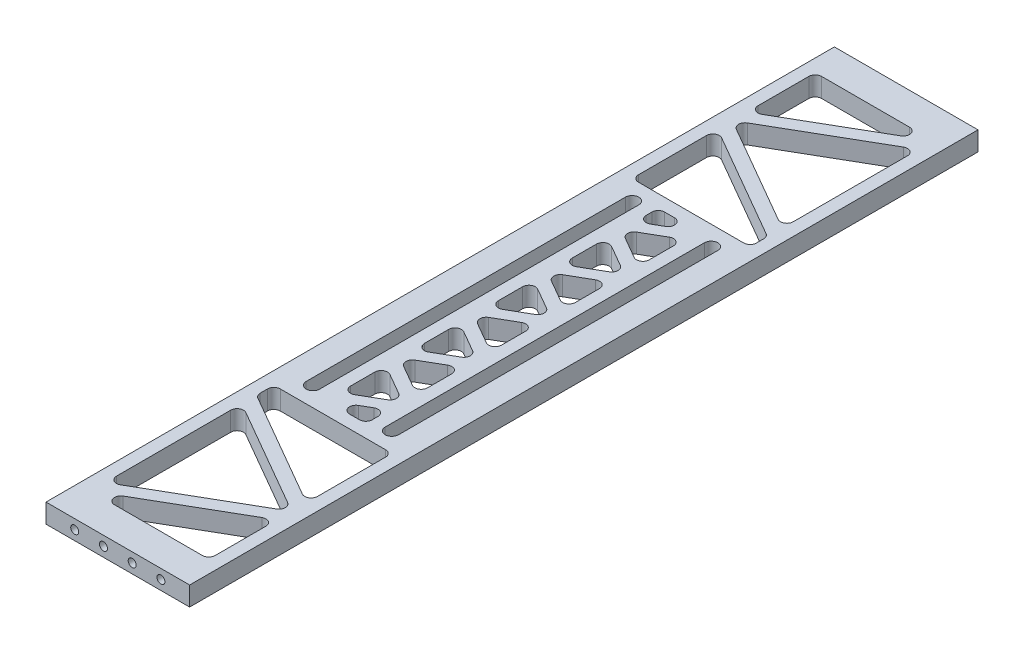
SolidWorks part; units mm, degrees
material "Сплав 2024"
ref_plane "Спереди" through (0, 0, 0) normal (0, 0, 1) x (1, 0, 0)
ref_plane "Сверху" through (0, 0, 0) normal (0, 1, 0) x (1, 0, 0)
ref_plane "Справа" through (0, 0, 0) normal (1, 0, 0) x (0, 0, -1)
sketch "Эскиз1" plane through (0, 0, 0) normal (0, 1, 0) x (1, 0, 0)
  line L2 (-15.9099, 15.9099) -> (15.9099, -15.9099) construction
  line L3 (15.9099, 15.9099) -> (-15.9099, -15.9099) construction
  line L4 (-22.5, 0) -> (-22.5, -247)
  line L5 (-22.5, -247) -> (22.5, -247)
  line L6 (22.5, 0) -> (22.5, -247)
  line L7 (-22.5, 0) -> (22.5, 0)
  dimension "D1" = 247
  dimension "D2" = 45
  dimension "D3" = 45
extrude "Бобышка-Вытянуть1" add sketch "Эскиз1" along normal blind 6
sketch "Эскиз2" plane through (0, 6, 0) normal (0, 1, 0) x (1, 0, 0)
  line L2 (0, 0) -> (0, -247) construction
  line L3 (-22.5, -247) -> (22.5, -247) construction
  line L4 (-12.3744, -135.8744) -> (12.3744, -111.1256) construction
  line L5 (-12.3744, -73.5) -> (-12.3744, -173.5) construction
  line L6 (-10.2744, -73.5) -> (-10.2744, -173.5)
  line L7 (-14.4744, -73.5) -> (-14.4744, -173.5)
  line L8 (-12.3744, -111.1256) -> (12.3744, -135.8744) construction
  line L9 (12.3744, -73.5) -> (12.3744, -173.5) construction
  line L10 (10.2744, -73.5) -> (10.2744, -173.5)
  line L11 (14.4744, -73.5) -> (14.4744, -173.5)
  line L13 (-22.5, -123.5) -> (22.5, -123.5) construction
  line L14 (-22.5, 0) -> (-22.5, -247) construction
  line L15 (22.5, -247) -> (22.5, 0) construction
  circle A0 centre (0, -123.5) radius 6 construction
  circle A1 centre (0, -123.5) radius 17.5 construction
  arc A2 (-10.2744, -73.5) -> (-14.4744, -73.5) centre (-12.3744, -73.5) ccw
  arc A3 (-14.4744, -173.5) -> (-10.2744, -173.5) centre (-12.3744, -173.5) ccw
  arc A4 (10.2744, -73.5) -> (14.4744, -73.5) centre (12.3744, -73.5) cw
  arc A5 (14.4744, -173.5) -> (10.2744, -173.5) centre (12.3744, -173.5) cw
  point P13 (12.3744, -123.5)
  point P18 (-12.3744, -123.5)
  point P37 (0, -123.5)
  dimension "D1" = 12
  dimension "D2" = 35
  dimension "D4" = 2.1
  dimension "D3" = 45
  dimension "D5" = 100
hole_wizard "Цековка для  винта с полукруглой головкой M31" [suppressed] positions "Эскиз4" profile "Эскиз5" counterbore size "M3" standard "Ansi Metric"
sketch "Эскиз4" plane through (0, 6, 0) normal (0, 1, 0) x (1, 0, 0)
  line L2 (-36.6046, 36.6046) -> (36.6046, -36.6046) construction
  line L3 (-12.3744, -12.3744) -> (12.3744, 12.3744) construction
  circle A0 centre (0, 0) radius 6 construction
  point P0 (-4.2426, 4.2426)
  point P6 (-4.2426, -4.2426)
  point P10 (4.2426, -4.2426)
  point P12 (4.2426, 4.2426)
sketch "Эскиз5" plane through (-4.2426, 6, -4.2426) normal (1, 0, 0) x (0, 0, 1)
  line L0 (0, 0) -> (0, 6)
  line L1 (0, 6) -> (1.7, 6)
  line L3 (1.7, 6) -> (1.7, 2)
  line L4 (1.7, 2) -> (3.35, 2)
  line L5 (3.35, 2) -> (3.35, 0)
  line L7 (3.35, 0) -> (0, 0)
  line L11 (0, -6.35) -> (0, 107.95) construction
  dimension "Диаметр сквозного отверстия" = 3.4
  dimension "Глубина сквозного отверстия" = 6
  dimension "Диаметр цековки" = 6.7
  dimension "Глубина цековки" = 2
hole_wizard "Отверстие обработанное метчиком M4x0.71" [suppressed] positions "Эскиз7" profile "Эскиз6" tap size "M4x0.7" standard "Ansi Metric"
sketch "Эскиз7" [suppressed] plane through (0, 4, 0) normal (0, 1, 0) x (1, 0, 0)
  line L0 (22.5, 0) -> (-22.5, 0) construction
  line L1 (0, 22.5) -> (0, -22.5) construction
  circle A0 centre (0, 0) radius 19.25 construction
  point P0 (-19.25, 0)
  point P6 (0, -19.25)
  point P10 (19.25, 0)
  point P12 (0, 19.25)
sketch "Эскиз6" plane through (-19.25, 4, 0) normal (1, 0, 0) x (0, 0, 1)
  line L0 (0, 0) -> (0, 4)
  line L1 (0, 4) -> (1.65, 4)
  line L2 (1.65, 4) -> (1.65, 0)
  line L5 (1.65, 0) -> (0, 0)
  line L11 (0, -6.35) -> (0, 107.95) construction
  dimension "Диаметр резьбы" = 3.3
  dimension "Глубина проходного сверла" = 4
extrude "Вырез-Вытянуть1" cut sketch "Эскиз2" against normal through all
sketch "Эскиз8" plane through (0, 0, 247) normal (0, 0, 1) x (1, 0, 0)
  line L0 (-22.5, 3) -> (22.5, 3) construction
  line L1 (-22.5, 6) -> (-22.5, 0) construction
  line L2 (22.5, 6) -> (22.5, 0) construction
  line L3 (-13.5, 6) -> (-13.5, 0) construction
  line L6 (-4.5, 6) -> (-4.5, 0) construction
  line L7 (4.5, 6) -> (4.5, 0) construction
  line L8 (13.5, 6) -> (13.5, 0) construction
  dimension "D1" = 45
  dimension "D2" = 9
  dimension "D3" = 9
  dimension "D4" = 9
  dimension "D5" = 9
sketch "Эскиз14" plane through (0, 6, 0) normal (0, 1, 0) x (1, 0, 0)
  line L0 (-22.5, -10) -> (22.5, -10) construction
  line L1 (-22.5, 0) -> (-22.5, -247) construction
  line L2 (22.5, -247) -> (22.5, 0) construction
  line L3 (-22.5, -237) -> (22.5, -237) construction
  line L4 (-22.5, -247) -> (22.5, -247) construction
  line L5 (22.5, 0) -> (-22.5, 0) construction
  line L6 (-18.5, 0) -> (-18.5, -247) construction
  line L7 (18.5, -247) -> (18.5, 0) construction
  line L8 (-22.5, -123.5) -> (22.5, -123.5) construction
  line L9 (-18.5, -10) -> (18.5, -10)
  line L10 (18.5, -10) -> (-18.5, -31.362)
  line L11 (-18.5, -31.362) -> (-18.5, -10)
  line L12 (-18.5, -35.9808) -> (18.5, -14.6188)
  line L13 (18.5, -14.6188) -> (18.5, -57.3427)
  line L14 (-18.5, -35.9808) -> (18.5, -57.3427)
  line L15 (-18.5, -40.5996) -> (-18.5, -67.4)
  line L16 (-6.2744, 0) -> (-6.2744, -247) construction
  line L17 (6.2744, -247) -> (6.2744, 0) construction
  line L19 (-10.2744, -173.5) -> (-10.2744, -73.5) construction
  line L20 (10.2744, -73.5) -> (10.2744, -173.5) construction
  line L21 (-22.5, -71.4) -> (22.5, -71.4) construction
  line L22 (-22.5, -175.6) -> (22.5, -175.6) construction
  line L23 (6.2744, -71.4) -> (-6.2744, -78.645)
  line L24 (6.2744, -75.7301) -> (-6.2744, -82.9751)
  line L25 (-6.2744, -82.9751) -> (6.2744, -90.2202)
  line L26 (6.2744, -90.2202) -> (6.2744, -75.7301)
  line L27 (-6.2744, -78.645) -> (-6.2744, -71.4)
  line L28 (-6.2744, -71.4) -> (6.2744, -71.4)
  line L29 (-6.2744, -87.3053) -> (6.2744, -94.5503)
  line L30 (6.2744, -94.5503) -> (-6.2744, -101.7953)
  line L31 (-6.2744, -101.7953) -> (-6.2744, -87.3053)
  line L32 (-6.2744, -106.1254) -> (6.2744, -98.8804)
  line L33 (6.2744, -98.8804) -> (6.2744, -113.3704)
  line L34 (6.2744, -113.3704) -> (-6.2744, -106.1254)
  line L35 (-6.2744, -110.4556) -> (6.2744, -117.7006)
  line L36 (6.2744, -117.7006) -> (-6.2744, -124.9456)
  line L37 (-6.2744, -124.9456) -> (-6.2744, -110.4556)
  line L38 (-6.2744, -129.2757) -> (6.2744, -122.0307)
  line L39 (6.2744, -122.0307) -> (6.2744, -136.5207)
  line L40 (6.2744, -136.5207) -> (-6.2744, -129.2757)
  line L41 (-6.2744, -133.6058) -> (6.2744, -140.8509)
  line L42 (6.2744, -140.8509) -> (-6.2744, -148.0959)
  line L43 (-6.2744, -148.0959) -> (-6.2744, -133.6058)
  line L44 (-6.2744, -152.426) -> (6.2744, -145.181)
  line L45 (6.2744, -145.181) -> (6.2744, -159.671)
  line L46 (6.2744, -159.671) -> (-6.2744, -152.426)
  line L47 (-6.2744, -156.7561) -> (6.2744, -164.0012)
  line L48 (6.2744, -164.0012) -> (-6.2744, -171.2462)
  line L49 (-6.2744, -171.2462) -> (-6.2744, -156.7561)
  line L50 (-6.2744, -175.5763) -> (6.2744, -168.3313)
  line L51 (6.2744, -168.3313) -> (6.2744, -175.5763)
  line L52 (6.2744, -175.5763) -> (-6.2744, -175.5763)
  line L53 (-18.5, -67.4) -> (18.5, -67.4)
  line L54 (18.5, -67.4) -> (18.5, -61.9615)
  line L55 (18.5, -61.9615) -> (-18.5, -40.5996)
  line L65 (0, -247) -> (0, -241.1177) construction
  line L67 (-18.5, -179.6) -> (-18.5, -185.0385)
  line L68 (-18.5, -232.3812) -> (-18.5, -189.6573)
  line L69 (18.5, -215.638) -> (18.5, -237)
  line L70 (18.5, -237) -> (-18.5, -237)
  line L71 (-18.5, -237) -> (18.5, -215.638)
  line L72 (18.5, -211.0192) -> (-18.5, -232.3812)
  line L73 (18.5, -211.0192) -> (-18.5, -189.6573)
  line L74 (-18.5, -185.0385) -> (18.5, -206.4004)
  line L75 (18.5, -206.4004) -> (18.5, -179.6)
  line L76 (18.5, -179.6) -> (-18.5, -179.6)
  arc A0 (-10.2744, -73.5) -> (-14.4744, -73.5) centre (-12.3744, -73.5) ccw construction
  arc A1 (10.2744, -173.5) -> (14.4744, -173.5) centre (12.3744, -173.5) ccw construction
  dimension "D1" = 10
  dimension "D2" = 10
  dimension "D3" = 4
  dimension "D4" = 4
  dimension "D5" = 4
  dimension "D6" = 4
  dimension "D7" = 30
  dimension "D8" = 3.75
  dimension "D9" = 60
  dimension "D10" = 3.75
  dimension "D11" = 60
  dimension "D12" = 3.75
  dimension "D13" = 60
  dimension "D14" = 3.75
  dimension "D15" = 60
  dimension "D16" = 3.75
  dimension "D17" = 3.75
  dimension "D18" = 3.75
  dimension "D19" = 3.75
  dimension "D20" = 60
  dimension "D21" = 60
  dimension "D22" = 60
  dimension "D23" = 60
  dimension "D24" = 3.75
  dimension "D25" = 30
  dimension "D26" = 4
  dimension "D27" = 60
  dimension "D28" = 4
  dimension "D29" = 4
  dimension "D30" = 4
  dimension "D31" = 4
  dimension "D32" = 4
  dimension "D33" = 30
  dimension "D34" = 60
extrude "Вырез-Вытянуть2" cut sketch "Эскиз14" against normal through all
fillet "Скругление1" radius 2 50 edges at (-6.2744, 3, 175.5763) (6.2744, 3, 175.5763) (6.2744, 3, 168.3313) (6.2744, 3, 145.181) (-6.2744, 3, 152.426) (-6.2744, 3, 156.7561) (6.2744, 3, 164.0012) (6.2744, 3, 159.671) (-6.2744, 3, 171.2462) (-6.2744, 3, 148.0959) (6.2744, 3, 140.8509) (-6.2744, 3, 133.6058) (6.2744, 3, 122.0307) (6.2744, 3, 136.5207) (-6.2744, 3, 129.2757) (6.2744, 3, 117.7006) (-6.2744, 3, 110.4556) (-6.2744, 3, 124.9456) (-6.2744, 3, 101.7953) (6.2744, 3, 94.5503) (-6.2744, 3, 106.1254) (6.2744, 3, 113.3704) (6.2744, 3, 98.8804) (-6.2744, 3, 87.3053) (6.2744, 3, 90.2202) (6.2744, 3, 75.7301) (-6.2744, 3, 82.9751) (-6.2744, 3, 78.645) (-6.2744, 3, 71.4) (6.2744, 3, 71.4) (-18.5, 3, 40.5996) (-18.5, 3, 67.4) (18.5, 3, 67.4) (18.5, 3, 61.9615) (18.5, 3, 57.3427) (18.5, 3, 14.6188) (-18.5, 3, 35.9808) (-18.5, 3, 31.362) (18.5, 3, 10) (-18.5, 3, 10) (18.5, 3, 237) (18.5, 3, 215.638) (-18.5, 3, 237) (-18.5, 3, 232.3812) (18.5, 3, 211.0192) (-18.5, 3, 189.6573) (18.5, 3, 206.4004) (-18.5, 3, 185.0385) (-18.5, 3, 179.6) (18.5, 3, 179.6)
chamfer "Фаска1" [suppressed] distance 1 angle 45
hole_wizard "Отверстие обработанное метчиком M3x0.52" positions "Эскиз12" profile "Эскиз11" tap size "M3x0.5" standard "Ansi Metric"
sketch "Эскиз12" plane through (0, 0, 0) normal (0, 0, -1) x (-1, 0, 0)
  line L0 (-13.5, 6) -> (-13.5, 0) construction
  line L1 (-4.5, 6) -> (-4.5, 0) construction
  line L2 (4.5, 6) -> (4.5, 0) construction
  line L3 (13.5, 6) -> (13.5, 0) construction
  point P0 (-13.5, 3)
  point P4 (-4.5, 3)
  point P8 (4.5, 3)
  point P12 (13.5, 3)
sketch "Эскиз11" plane through (13.5, 3, 0) normal (1, 0, 0) x (0, 1, 0)
  line L0 (0, 0) -> (0, 9.2511)
  line L1 (0, 9.2511) -> (1.25, 8.5)
  line L2 (1.25, 8.5) -> (1.25, 0)
  line L5 (1.25, 0) -> (0, 0)
  line L10 (0, 9.2511) -> (-1.25, 8.5) construction
  line L11 (0, -6.35) -> (0, 107.95) construction
  dimension "Диаметр сверла" = 2.5
  dimension "Глубина сверла" = 8.5
  dimension "Угол заточки сверла" = 118
cosmetic thread "Отверстие резьбы5" parameters "D1"=6, "D2"=3
cosmetic thread "Отверстие резьбы6" parameters "D1"=6, "D2"=3
cosmetic thread "Отверстие резьбы7" parameters "D1"=6, "D2"=3
cosmetic thread "Отверстие резьбы8" parameters "D1"=6, "D2"=3
hole_wizard "Отверстие обработанное метчиком M3x0.51" positions "Эскиз10" profile "Эскиз9" tap size "M3x0.5" standard "Ansi Metric"
sketch "Эскиз10" plane through (0, 0, 247) normal (0, 0, 1) x (1, 0, 0)
  line L0 (-13.5, 6) -> (-13.5, 0) construction
  line L1 (-4.5, 6) -> (-4.5, 0) construction
  line L2 (4.5, 6) -> (4.5, 0) construction
  line L3 (13.5, 6) -> (13.5, 0) construction
  point P0 (-13.5, 3)
  point P4 (-4.5, 3)
  point P8 (4.5, 3)
  point P12 (13.5, 3)
sketch "Эскиз9" plane through (-13.5, 3, 247) normal (1, 0, 0) x (0, -1, 0)
  line L0 (0, 0) -> (0, 9.2511)
  line L1 (0, 9.2511) -> (1.25, 8.5)
  line L2 (1.25, 8.5) -> (1.25, 0)
  line L5 (1.25, 0) -> (0, 0)
  line L10 (0, 9.2511) -> (-1.25, 8.5) construction
  line L11 (0, -6.35) -> (0, 107.95) construction
  dimension "Диаметр сверла" = 2.5
  dimension "Глубина сверла" = 8.5
  dimension "Угол заточки сверла" = 118
cosmetic thread "Отверстие резьбы1" parameters "D1"=6, "D2"=3
cosmetic thread "Отверстие резьбы2" parameters "D1"=6, "D2"=3
cosmetic thread "Отверстие резьбы3" parameters "D1"=6, "D2"=3
cosmetic thread "Отверстие резьбы4" parameters "D1"=6, "D2"=3
equation "\"D2@Эскиз8\"=\"D1@Эскиз8\"/5"
equation "\"D3@Эскиз8\"=\"D2@Эскиз8\""
equation "\"D4@Эскиз8\"=\"D2@Эскиз8\""
equation "\"D5@Эскиз8\"=\"D2@Эскиз8\""
equation "\"D10@Эскиз14\"=\"D8@Эскиз14\""
equation "\"D12@Эскиз14\"=\"D8@Эскиз14\""
equation "\"D14@Эскиз14\"=\"D8@Эскиз14\""
equation "\"D16@Эскиз14\"=\"D8@Эскиз14\""
equation "\"D17@Эскиз14\"=\"D16@Эскиз14\""
equation "\"D18@Эскиз14\"=\"D16@Эскиз14\""
equation "\"D19@Эскиз14\"=\"D18@Эскиз14\""
equation "\"D9@Эскиз14\"=\"D7@Эскиз14\"*2"
equation "\"D11@Эскиз14\"=\"D9@Эскиз14\""
equation "\"D13@Эскиз14\"=\"D9@Эскиз14\""
equation "\"D15@Эскиз14\"=\"D9@Эскиз14\""
equation "\"D20@Эскиз14\"=\"D15@Эскиз14\""
equation "\"D21@Эскиз14\"=\"D15@Эскиз14\""
equation "\"D22@Эскиз14\"=\"D15@Эскиз14\""
equation "\"D23@Эскиз14\"=\"D15@Эскиз14\""
equation "\"D24@Эскиз14\"=\"D19@Эскиз14\""
equation "\"D27@Эскиз14\"=\"D25@Эскиз14\"*2"
equation "\"D33@Эскиз14\"=\"D25@Эскиз14\""
equation "\"D34@Эскиз14\"=\"D33@Эскиз14\"*2"
